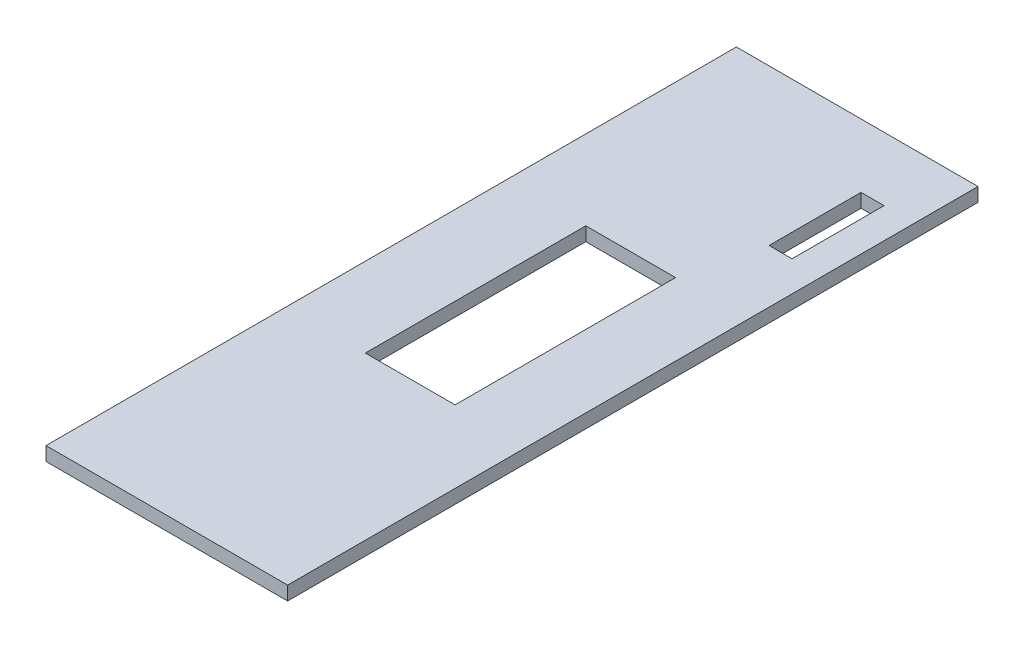
SolidWorks part; units mm, degrees
ref_plane "Front Plane" through (0, 0, 0) normal (0, 0, 1) x (1, 0, 0)
ref_plane "Top Plane" through (0, 0, 0) normal (0, 1, 0) x (1, 0, 0)
ref_plane "Right Plane" through (0, 0, 0) normal (1, 0, 0) x (0, 0, -1)
sketch "Sketch1" plane through (0, 0, 0) normal (0, 0, 1) x (1, 0, 0)
  line L1 (-30.1903, 8.7685) -> (74.8097, 8.7685)
  line L2 (-30.1903, 8.7685) -> (-30.1903, 2.7685)
  line L3 (-30.1903, 2.7685) -> (74.8097, 2.7685)
  line L4 (74.8097, 8.7685) -> (74.8097, 2.7685)
  dimension "D1" = 105
  dimension "D2" = 6
extrude "Boss-Extrude1" add sketch "Sketch1" along normal blind 300
sketch "Sketch2" plane through (0, 8.7685, 0) normal (0, 1, 0) x (1, 0, 0)
  line L0 (74.8097, 0) -> (-30.1903, 0) construction
  line L1 (51.6097, -27.62) -> (61.6097, -27.62)
  line L2 (51.6097, -27.62) -> (51.6097, -67.62)
  line L3 (51.6097, -67.62) -> (61.6097, -67.62)
  line L4 (61.6097, -27.62) -> (61.6097, -67.62)
  line L5 (74.8097, -300) -> (74.8097, 0) construction
  dimension "D1" = 27.62
  dimension "D2" = 13.2
  dimension "D3" = 10
  dimension "D4" = 40
extrude "Cut-Extrude1" cut sketch "Sketch2" against normal blind 10
sketch "Sketch3" plane through (0, 8.7685, 0) normal (0, 1, 0) x (1, 0, 0)
  line L0 (74.8097, -300) -> (74.8097, 0) construction
  line L1 (4.3797, -100) -> (43.3797, -100)
  line L2 (4.3797, -100) -> (4.3797, -195.8)
  line L3 (4.3797, -195.8) -> (43.3797, -195.8)
  line L4 (43.3797, -100) -> (43.3797, -195.8)
  line L5 (74.8097, 0) -> (-30.1903, 0) construction
  dimension "D1" = 31.43
  dimension "D2" = 100
  dimension "D3" = 95.8
  dimension "D4" = 39
extrude "Cut-Extrude2" cut sketch "Sketch3" against normal blind 10
